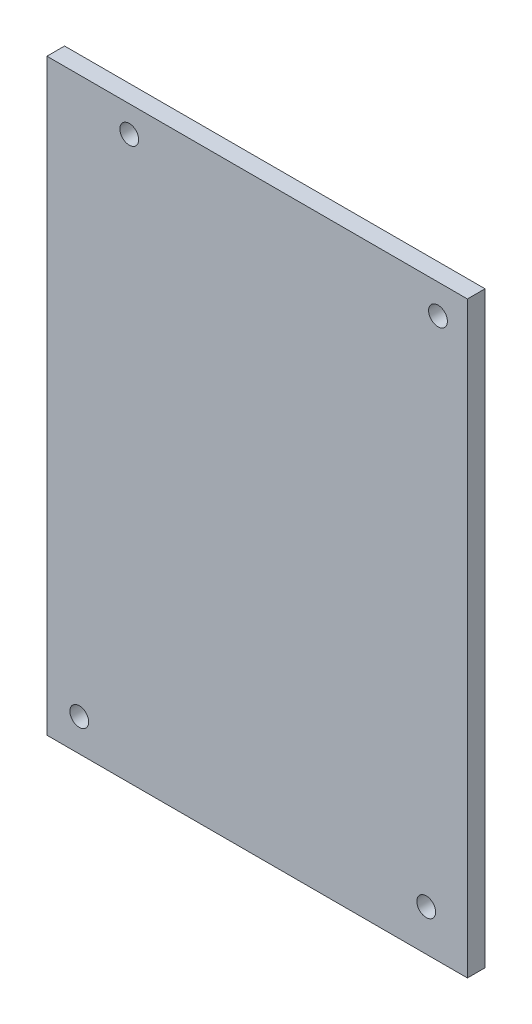
SolidWorks part; units mm, degrees
ref_plane "Front Plane" through (0, 0, 0) normal (0, 0, 1) x (1, 0, 0)
ref_plane "Top Plane" through (0, 0, 0) normal (0, 1, 0) x (1, 0, 0)
ref_plane "Right Plane" through (0, 0, 0) normal (1, 0, 0) x (0, 0, -1)
sketch "Sketch1" plane through (0, 0, 0) normal (0, 0, 1) x (1, 0, 0)
  line L1 (0, 100) -> (71.5, 100)
  line L2 (0, 100) -> (0, 0)
  line L3 (0, 0) -> (71.5, 0)
  line L4 (71.5, 100) -> (71.5, 0)
  circle A0 centre (66.5, 95) radius 1.6
  circle A1 centre (64.5, 7) radius 1.6
  circle A2 centre (5.5, 5.5) radius 1.6
  circle A3 centre (14, 95.5) radius 1.6
  dimension "D5" = 3.2
  dimension "D6" = 3.2
  dimension "D7" = 3.2
  dimension "D8" = 3.2
  dimension "D12" = 7
  dimension "D13" = 5
  dimension "D14" = 5
  dimension "D1" = 71.5
  dimension "D2" = 100
  dimension "D3" = 4.5
  dimension "D4" = 14
  dimension "D9" = 5.5
  dimension "D10" = 5.5
  dimension "D11" = 7
extrude "Boss-Extrude1" add sketch "Sketch1" along normal blind 3
